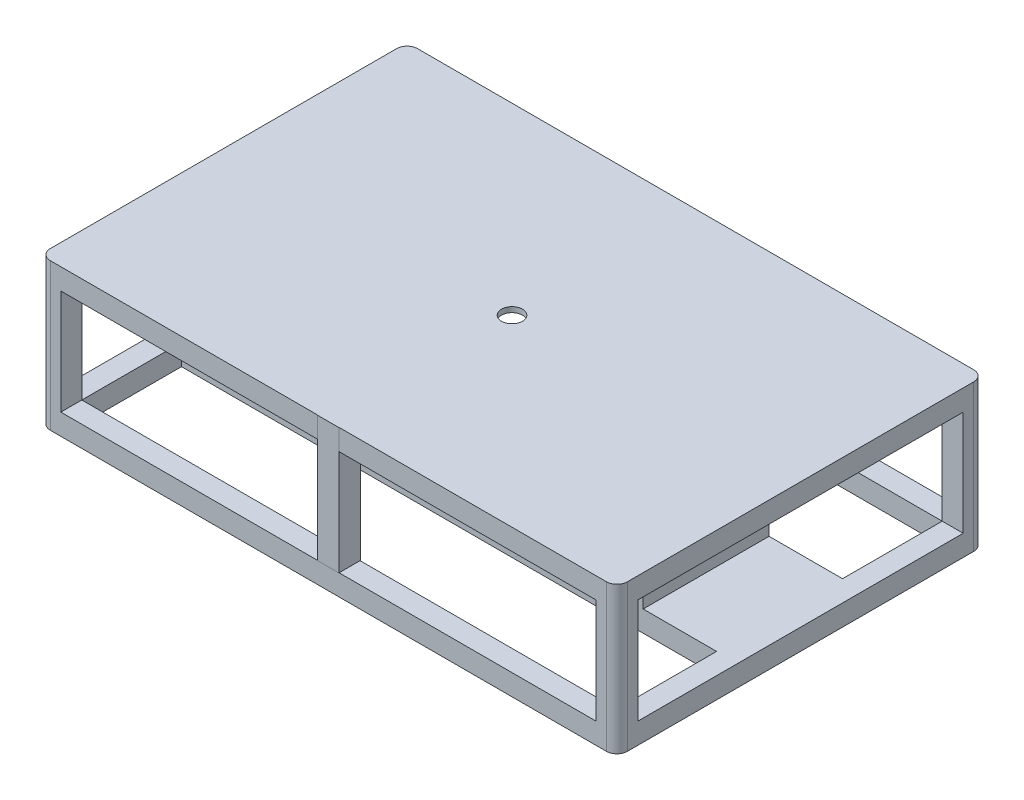
SolidWorks part; units mm, degrees
ref_plane "Front Plane" through (0, 0, 0) normal (0, 0, 1) x (1, 0, 0)
ref_plane "Top Plane" through (0, 0, 0) normal (0, 1, 0) x (1, 0, 0)
ref_plane "Right Plane" through (0, 0, 0) normal (1, 0, 0) x (0, 0, -1)
sketch "Sketch1" plane through (0, 0, 0) normal (0, 1, 0) x (1, 0, 0)
  line L0 (-255, 155) -> (255, 155)
  line L1 (-275, -175) -> (275, -175)
  line L2 (-275, -175) -> (-275, 175)
  line L3 (-275, 175) -> (275, 175)
  line L4 (275, -175) -> (275, 175)
  line L5 (-275, -175) -> (275, 175) construction
  line L6 (-275, 175) -> (275, -175) construction
  line L7 (255, -155) -> (255, 155)
  line L8 (-255, -155) -> (255, -155)
  line L9 (-255, -155) -> (-255, 155)
  point P0 (0, 0)
  dimension "D1" = 350
  dimension "D2" = 550
  dimension "D3" = 20
extrude "Boss-Extrude1" add sketch "Sketch1" along normal blind 20
sketch "Sketch3" plane through (0, 20, 0) normal (0, 1, 0) x (1, 0, 0)
  line L0 (0, 155) -> (0, 175) construction
  line L1 (-255, 155) -> (-275, 155)
  line L2 (-255, 155) -> (-255, 175)
  line L3 (-255, 175) -> (-275, 175)
  line L4 (-275, 155) -> (-275, 175)
  line L5 (-255, -155) -> (-275, -155)
  line L6 (-255, -155) -> (-255, -175)
  line L7 (-255, -175) -> (-275, -175)
  line L8 (-275, -155) -> (-275, -175)
  line L9 (255, -155) -> (275, -155)
  line L10 (255, -155) -> (255, -175)
  line L11 (255, -175) -> (275, -175)
  line L12 (275, -155) -> (275, -175)
  line L13 (255, 155) -> (275, 155)
  line L14 (255, 155) -> (255, 175)
  line L15 (255, 175) -> (275, 175)
  line L16 (275, 155) -> (275, 175)
  line L17 (255, 155) -> (-255, 155) construction
  line L18 (275, 175) -> (-275, 175) construction
  line L20 (-255, -155) -> (255, -155) construction
  line L21 (0, -155) -> (0, -175) construction
  line L22 (-275, -175) -> (275, -175) construction
  line L23 (-10.0112, 154.9888) -> (10.0112, 154.9888)
  line L24 (-10.0112, 154.9888) -> (-10.0112, 175.0112)
  line L25 (-10.0112, 175.0112) -> (10.0112, 175.0112)
  line L26 (10.0112, 154.9888) -> (10.0112, 175.0112)
  line L27 (-10.0112, 154.9888) -> (10.0112, 175.0112) construction
  line L28 (-10.0112, 175.0112) -> (10.0112, 154.9888) construction
  line L29 (-10.2167, -175.2167) -> (10.2167, -175.2167)
  line L30 (-10.2167, -175.2167) -> (-10.2167, -154.7833)
  line L31 (-10.2167, -154.7833) -> (10.2167, -154.7833)
  line L32 (10.2167, -175.2167) -> (10.2167, -154.7833)
  line L33 (-10.2167, -175.2167) -> (10.2167, -154.7833) construction
  line L34 (-10.2167, -154.7833) -> (10.2167, -175.2167) construction
  point P36 (0, 165)
  point P41 (0, -165)
extrude "Boss-Extrude2" add sketch "Sketch3" along normal blind 120
sketch "Sketch4" plane through (0, 140, 0) normal (0, 1, 0) x (1, 0, 0)
  line L0 (-255, 155) -> (-255, -155)
  line L1 (-275, 175) -> (275, 175)
  line L2 (-275, 175) -> (-275, -175)
  line L3 (-275, -175) -> (275, -175)
  line L4 (275, 175) -> (275, -175)
  line L5 (-255, -155) -> (255, -155)
  line L6 (255, 155) -> (255, -155)
  line L7 (-255, 155) -> (255, 155)
  dimension "D1" = 20
extrude "Boss-Extrude3" add sketch "Sketch4" against normal blind 20
sketch "Sketch5" plane through (0, 140, 0) normal (0, 1, 0) x (1, 0, 0)
  line L1 (-275, 175) -> (275, 175)
  line L2 (-275, 175) -> (-275, -175)
  line L3 (-275, -175) -> (275, -175)
  line L4 (275, 175) -> (275, -175)
extrude "Boss-Extrude4" add sketch "Sketch5" against normal blind 5
sketch "Sketch6" plane through (0, 0, 0) normal (0, -1, 0) x (1, 0, 0)
  line L0 (275, 175) -> (275, -175) construction
  line L1 (-275, -60) -> (275, -60)
  line L2 (-275, -60) -> (-275, 60)
  line L3 (-275, 60) -> (275, 60)
  line L4 (275, -60) -> (275, 60)
  line L5 (-275, -60) -> (275, 60) construction
  line L6 (-275, 60) -> (275, -60) construction
  point P0 (0, 0)
  dimension "D1" = 120
extrude "Boss-Extrude5" add sketch "Sketch6" against normal blind 20
sketch "Sketch7" plane through (0, 0, 60) normal (0, 0, 1) x (1, 0, 0)
  line L0 (0, 0) -> (0, 20) construction
  line L1 (-10.2167, 20) -> (10.2167, 20) construction
  line L2 (0, 20) -> (-159.9395, 20) construction
  line L3 (-255, 20) -> (-10.2167, 20) construction
  line L4 (-159.9395, 20) -> (160.0175, 20) construction
  line L5 (10.2167, 20) -> (255, 20) construction
  line L6 (-275, 0) -> (275, 0) construction
  line L7 (-184.8736, 40) -> (-135.0053, 40)
  line L8 (-184.8736, 40) -> (-184.8736, 0)
  line L9 (-184.8736, 0) -> (-135.0053, 0)
  line L10 (-135.0053, 40) -> (-135.0053, 0)
  line L11 (-184.8736, 40) -> (-135.0053, 0) construction
  line L12 (-184.8736, 0) -> (-135.0053, 40) construction
  line L14 (135.0366, 40) -> (184.9984, 40)
  line L15 (135.0366, 40) -> (135.0366, 0)
  line L16 (135.0366, 0) -> (184.9984, 0)
  line L17 (184.9984, 40) -> (184.9984, 0)
  line L18 (135.0366, 40) -> (184.9984, 0) construction
  line L19 (135.0366, 0) -> (184.9984, 40) construction
extrude "Boss-Extrude6" add sketch "Sketch7" against normal up to surface (120 mm away) up to face at (0, 10, -60)
sketch "Sketch8" plane through (0, 0, 60) normal (0, 0, 1) x (1, 0, 0)
  line L0 (-184.8736, 40) -> (-135.0053, 0) construction
  line L1 (-135.0053, 40) -> (-184.8736, 40) construction
  line L2 (-135.0053, 0) -> (135.0366, 0) construction
  line L5 (135.0366, 0) -> (184.9984, 40) construction
  line L6 (184.9984, 40) -> (135.0366, 40) construction
  line L7 (135.0366, 20) -> (135.0366, 0) construction
  line L8 (10.2167, 20) -> (255, 20) construction
  line L9 (-275, 0) -> (275, 0) construction
  line L10 (-135.0053, 40) -> (-135.0053, 0) construction
  line L11 (-135.0053, 20) -> (-135.0053, 40) construction
  circle A0 centre (160.0175, 20) radius 5
  circle A1 centre (-159.9395, 20) radius 5
  point P6 (-133.1806, 0)
extrude "Cut-Extrude1" cut sketch "Sketch8" against normal blind 181
fillet "Fillet1" radius 10 4 edges at (-275, 70, -175) (275, 70, -175) (275, 70, 175) (-275, 70, 175)
sketch "Sketch9" plane through (0, 140, 0) normal (0, 1, 0) x (1, 0, 0)
  circle A0 centre (0, 0) radius 10
extrude "Cut-Extrude2" cut sketch "Sketch9" against normal blind 43
